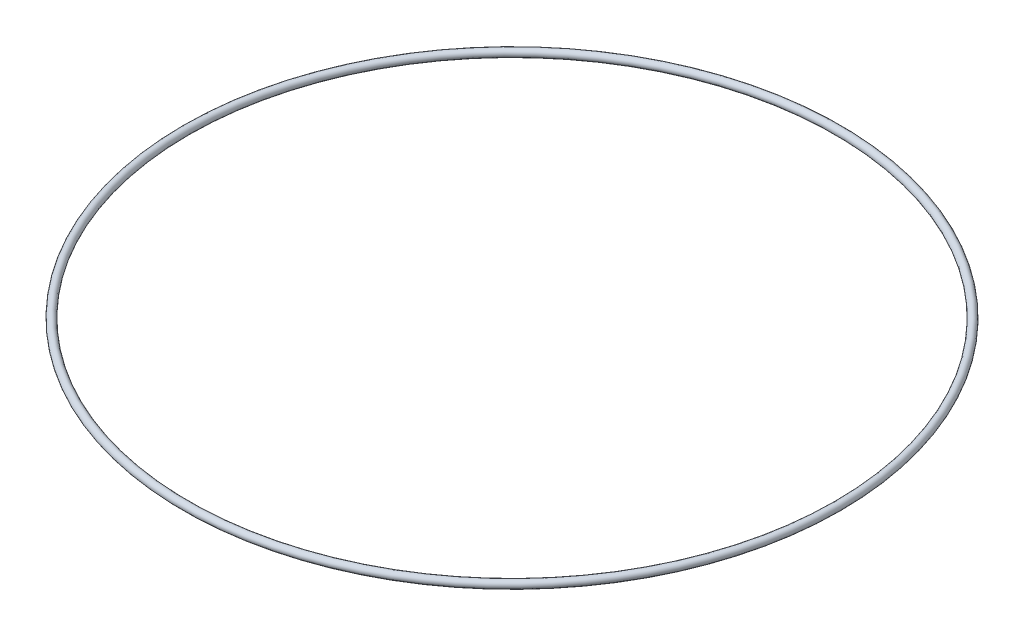
SolidWorks part; units mm, degrees
ref_plane "Front Plane" through (0, 0, 0) normal (0, 0, 1) x (1, 0, 0)
ref_plane "Top Plane" through (0, 0, 0) normal (0, 1, 0) x (1, 0, 0)
ref_plane "Right Plane" through (0, 0, 0) normal (1, 0, 0) x (0, 0, -1)
sketch "Sketch2" plane through (0, 0, 0) normal (0, 0, 1) x (1, 0, 0)
  line L0 (0, 0) -> (75, 0) construction
  circle A0 centre (75, 0) radius 0.889
  dimension "D1" = 1.778
  dimension "D2" = 75
sketch "Sketch3" plane through (0, 0, 0) normal (0, 1, 0) x (1, 0, 0)
  circle A0 centre (0, 0) radius 75
  dimension "D1" = 150
sweep "Sweep1" add profiles "Sketch2" path "Sketch3"
